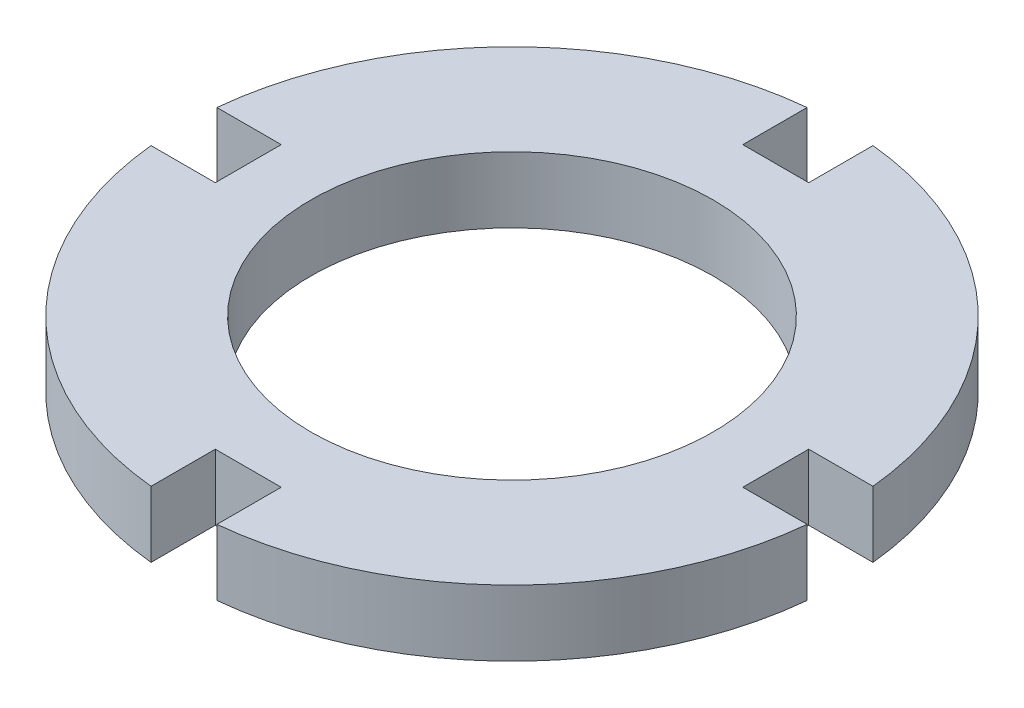
SolidWorks part; units mm, degrees
ref_plane "Front Plane" through (0, 0, 0) normal (0, 0, 1) x (1, 0, 0)
ref_plane "Top Plane" through (0, 0, 0) normal (0, 1, 0) x (1, 0, 0)
ref_plane "Right Plane" through (0, 0, 0) normal (1, 0, 0) x (0, 0, -1)
sketch "Sketch1" plane through (0, 0, 0) normal (0, 1, 0) x (1, 0, 0)
  circle A0 centre (0, 0) radius 25.4
  dimension "D1" = 50.8
extrude "Boss-Extrude1" add sketch "Sketch1" along normal blind 5.08
sketch "Sketch2" plane through (0, 5.08, 0) normal (0, 1, 0) x (1, 0, 0)
  circle A0 centre (0, 0) radius 15.494
  dimension "D1" = 30.988
extrude "Cut-Extrude1" cut sketch "Sketch2" against normal blind 50.8
sketch "Sketch3" plane through (0, 0, 0) normal (0, -1, 0) x (1, 0, 0)
  line L1 (2.54, -30.48) -> (-2.54, -30.48)
  line L2 (2.54, -30.48) -> (2.54, -20.32)
  line L3 (2.54, -20.32) -> (-2.54, -20.32)
  line L4 (-2.54, -30.48) -> (-2.54, -20.32)
  line L5 (2.54, -30.48) -> (-2.54, -20.32) construction
  line L6 (2.54, -20.32) -> (-2.54, -30.48) construction
  circle A0 centre (0, 0) radius 25.4 construction
  point P0 (0, -25.4)
  dimension "D2" = 5.08
  dimension "D1" = 5.08
extrude "Cut-Extrude2" cut sketch "Sketch3" against normal blind 50.8
pattern_circular "CirPattern1" count 4 over 360 about axis through (0, 0, 0) along (0, 1, 0) of "Cut-Extrude2"
